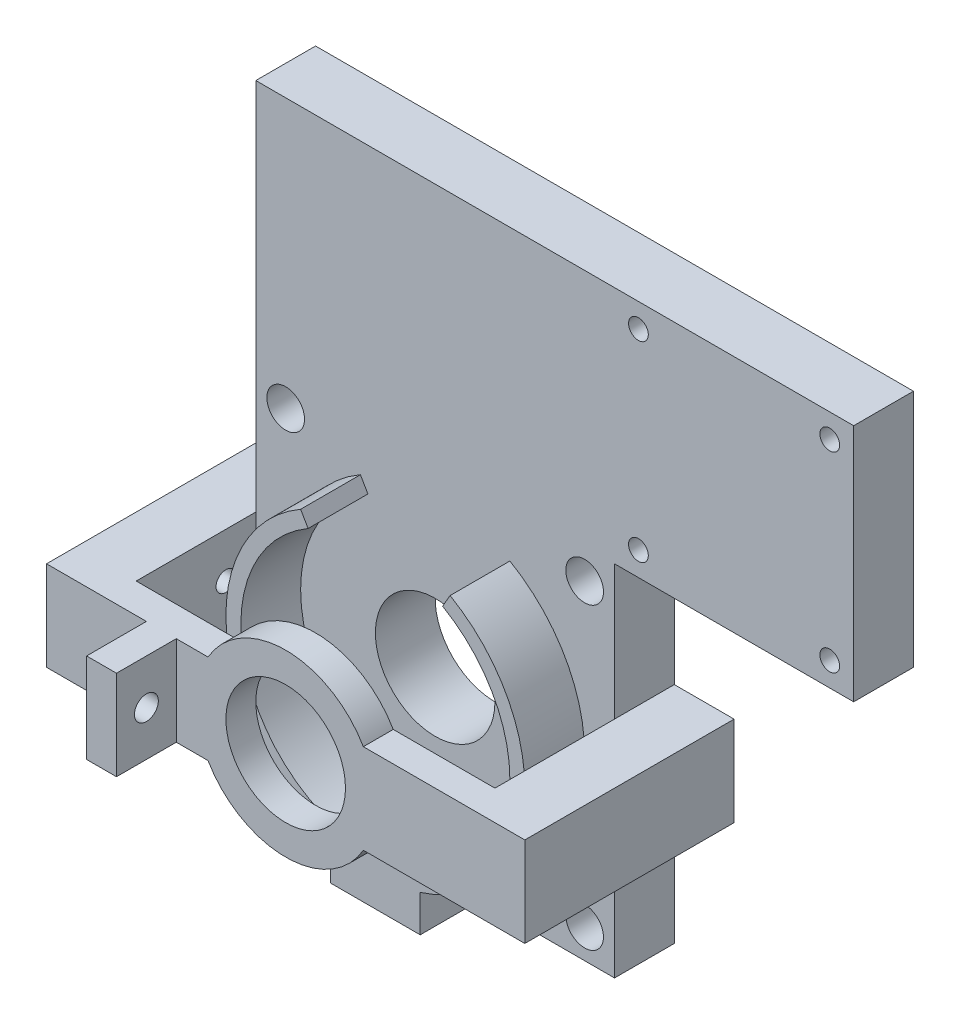
SolidWorks part; units mm, degrees
ref_plane "Front Plane" through (0, 0, 0) normal (0, 0, 1) x (1, 0, 0)
ref_plane "Top Plane" through (0, 0, 0) normal (0, 1, 0) x (1, 0, 0)
ref_plane "Right Plane" through (0, 0, 0) normal (1, 0, 0) x (0, 0, -1)
sketch "Sketch1" plane through (0, 0, 0) normal (0, 0, 1) x (1, 0, 0)
  line L1 (-30, 30) -> (30, 30)
  line L2 (-30, 30) -> (-30, -30)
  line L3 (-30, -30) -> (30, -30)
  line L4 (30, 30) -> (30, -30)
  line L5 (-30, 30) -> (30, -30) construction
  line L6 (-30, -30) -> (30, 30) construction
  point P0 (0, 0)
  point P5 (0, 0)
  dimension "D1" = 60
extrude "Boss-Extrude1" add sketch "Sketch1" along normal blind 10
sketch "Sketch2" plane through (0, 0, 10) normal (0, 0, 1) x (1, 0, 0)
  line L0 (-11.25, 19.4856) -> (-12.5, 21.6506)
  line L1 (11.25, 19.4856) -> (12.5, 21.6506)
  line L2 (0, 0) -> (25, 0) construction
  line L3 (-30, -30) -> (30, -30) construction
  line L4 (-7.5, -30) -> (7.5, -30)
  line L5 (-7.5, -30) -> (-7.5, -23.8485)
  line L7 (7.5, -30) -> (7.5, -23.8485)
  arc A0 (-11.25, 19.4856) -> (11.25, 19.4856) centre (0, 0) ccw
  arc A1 (-12.5, 21.6506) -> (-7.5, -23.8485) centre (0, 0) ccw
  arc A2 (7.5, -23.8485) -> (12.5, 21.6506) centre (0, 0) ccw
  point P13 (0, -30)
  point P14 (0, -30)
  point P15 (0, 0)
  dimension "D1" = 45
  dimension "D2" = 50
  dimension "D3" = 60
  dimension "D4" = 60
  dimension "D5" = 15
  dimension "D6" = 120
extrude "Boss-Extrude2" add sketch "Sketch2" along normal blind 10
sketch "Sketch3" plane through (0, 0, 10) normal (0, 0, 1) x (1, 0, 0)
  circle A0 centre (0, 0) radius 10
  dimension "D1" = 20
extrude "Cut-Extrude1" cut sketch "Sketch3" against normal through all
sketch "Sketch4" plane through (0, 0, 10) normal (0, 0, 1) x (1, 0, 0)
  line L1 (25, -25) -> (-25, -25) construction
  line L2 (25, -25) -> (25, 25) construction
  line L3 (25, 25) -> (-25, 25) construction
  line L4 (-25, -25) -> (-25, 25) construction
  line L5 (25, -25) -> (-25, 25) construction
  line L6 (25, 25) -> (-25, -25) construction
  circle A0 centre (-25, 25) radius 3.15
  circle A1 centre (25, 25) radius 3.15
  circle A2 centre (25, -25) radius 3.15
  circle A3 centre (-25, -25) radius 3.15
  point P0 (0, 0)
  dimension "D3" = 6.3
  dimension "D1" = 50
  dimension "D2" = 50
extrude "Cut-Extrude2" cut sketch "Sketch4" against normal through all
sketch "Sketch5" plane through (0, 0, 0) normal (0, 0, -1) x (-1, 0, 0)
  line L0 (30, 30) -> (30, -30) construction
  line L1 (30, 7.5) -> (40, 7.5)
  line L2 (30, 7.5) -> (30, -7.5)
  line L3 (30, -7.5) -> (40, -7.5)
  line L4 (40, 7.5) -> (40, -7.5)
  point P6 (30, 0)
  point P7 (30, 0)
  dimension "D1" = 10
  dimension "D2" = 15
extrude "Boss-Extrude3" add sketch "Sketch5" against normal blind 45
ref_plane "Plane1" through (0, 0, 0) normal (-1, 0, 0) x (0, 0, 1)
mirror "Mirror1" about plane through (0, 0, 0) normal (-1, 0, 0) of "Boss-Extrude3"
ref_plane "Plane2" through (0, 0, 30) normal (0, 0, 1) x (1, 0, 0)
sketch "Sketch6" plane through (0, 0, 30) normal (0, 0, 1) x (1, 0, 0)
  line L1 (30, -7.5) -> (12.9904, -7.5)
  line L2 (30, -7.5) -> (30, 7.5)
  line L3 (30, 7.5) -> (12.9904, 7.5)
  line L4 (-30, -7.5) -> (-30, 7.5)
  line L5 (30, -7.5) -> (-30, 7.5) construction
  line L6 (30, 7.5) -> (-30, -7.5) construction
  line L7 (-40, -7.5) -> (-40, 7.5) construction
  line L8 (-12.9904, 7.5) -> (-30, 7.5)
  line L9 (-12.9904, -7.5) -> (-30, -7.5)
  line L10 (6.6144, -7.5) -> (-6.6144, -7.5)
  circle A0 centre (0, 0) radius 10
  arc A1 (-12.9904, -7.5) -> (12.9904, -7.5) centre (0, 0) ccw
  arc A2 (12.9904, 7.5) -> (-12.9904, 7.5) centre (0, 0) ccw
  dimension "D1" = 20
  dimension "D2" = 30
extrude "Boss-Extrude4" add sketch "Sketch6" along normal blind 5 contours L3 A2 L8 L4 L9 A1 L1 L2 A0
sketch "Sketch7" plane through (0, -30, 0) normal (0, -1, 0) x (-1, 0, 0)
  line L0 (7.5, -20) -> (-7.5, -10) construction
  circle A0 centre (0, -15) radius 1.65
  point P6 (0, -15)
  dimension "D1" = 3.3
extrude "Cut-Extrude4" cut sketch "Sketch7" against normal up to next
sketch "Sketch8" plane through (0, 0, 35) normal (0, 0, 1) x (1, 0, 0)
  line L0 (-12.9904, -7.5) -> (-30, -7.5) construction
  line L1 (-30, -7.5) -> (-18.3, -7.5)
  line L2 (-30, -7.5) -> (-30, 7.5)
  line L3 (-30, 7.5) -> (-18.3, 7.5)
  line L4 (-18.3, -7.5) -> (-18.3, 7.5)
  line L5 (-30, -7.5) -> (-30, 7.5) construction
  line L6 (-12.9904, 7.5) -> (-30, 7.5) construction
  circle A0 centre (0, 0) radius 10 construction
  dimension "D1" = 18.3
extrude "Boss-Extrude5" add sketch "Sketch8" along normal up to surface (10 mm away) up to face at (-35, 0, 45)
sketch "Sketch9" plane through (0, -7.5, 0) normal (0, -1, 0) x (1, 0, 0)
  line L0 (-40, 45) -> (-40, 0) construction
  line L1 (-40, 45) -> (-23.3, 45)
  line L2 (-40, 45) -> (-40, 35)
  line L3 (-40, 35) -> (-23.3, 35)
  line L4 (-23.3, 45) -> (-23.3, 35)
  line L5 (-18.3, 45) -> (-40, 45) construction
  line L6 (30, 35) -> (12.9904, 35) construction
  line L7 (-18.3, 45) -> (-18.3, 35) construction
  dimension "D1" = 5
extrude "Cut-Extrude5" cut sketch "Sketch9" against normal through all
sketch "Sketch11" plane through (-23.3, 0, 0) normal (-1, 0, 0) x (0, 0, 1)
  line L0 (45, 7.5) -> (35, -7.5) construction
  circle A0 centre (40, 0) radius 2
  point P6 (0, 0)
  point P7 (40, 0)
  dimension "D1" = 4
extrude "Cut-Extrude6" cut sketch "Sketch11" against normal up to next
sketch "Sketch12" plane through (30, 0, 0) normal (-1, 0, 0) x (0, 0, 1)
  line L1 (35, 7.5) -> (45, 7.5)
  line L2 (35, 7.5) -> (35, -7.5)
  line L3 (35, -7.5) -> (45, -7.5)
  line L4 (45, 7.5) -> (45, -7.5)
extrude "Cut-Extrude7" cut sketch "Sketch12" against normal up to surface (10 mm away) up to face at (40, 0, 22.5)
sketch "Sketch15" plane through (-40, 0, 0) normal (-1, 0, 0) x (0, 0, 1)
  line L0 (0, -7.5) -> (0, 7.5) construction
  circle A0 centre (5, 0) radius 1.65
  dimension "D1" = 3.3
  dimension "D2" = 5
extrude "Cut-Extrude8" cut sketch "Sketch15" against normal blind 10
pattern_linear "LPattern1" count 3 spacing 10 along (0, 0, 1) of "Cut-Extrude8"
sketch "Sketch16" plane through (0, 0, 0) normal (0, 0, -1) x (-1, 0, 0)
  line L0 (-30, 7.5) -> (-30, 30) construction
  line L1 (30, 30) -> (-70, 30)
  line L2 (30, 30) -> (30, 70)
  line L3 (30, 70) -> (-70, 70)
  line L4 (-70, 30) -> (-70, 70)
  dimension "D1" = 40
  dimension "D2" = 40
extrude "Boss-Extrude6" add sketch "Sketch16" against normal up to surface (10 mm away) up to face at (-21.85, -25, 10)
sketch "Sketch17" plane through (0, 0, 10) normal (0, 0, 1) x (1, 0, 0)
  line L0 (70, 70) -> (30, 30) construction
  line L2 (34, 66) -> (66, 66) construction
  line L3 (34, 66) -> (34, 34) construction
  line L4 (34, 34) -> (66, 34) construction
  line L5 (66, 66) -> (66, 34) construction
  line L6 (34, 66) -> (66, 34) construction
  line L7 (34, 34) -> (66, 66) construction
  circle A0 centre (66, 34) radius 1.65
  circle A1 centre (66, 66) radius 1.65
  circle A2 centre (34, 66) radius 1.65
  circle A3 centre (34, 34) radius 1.65
  point P4 (50, 50)
  dimension "D2" = 3.3
  dimension "D1" = 32
extrude "Cut-Extrude9" cut sketch "Sketch17" against normal through all
